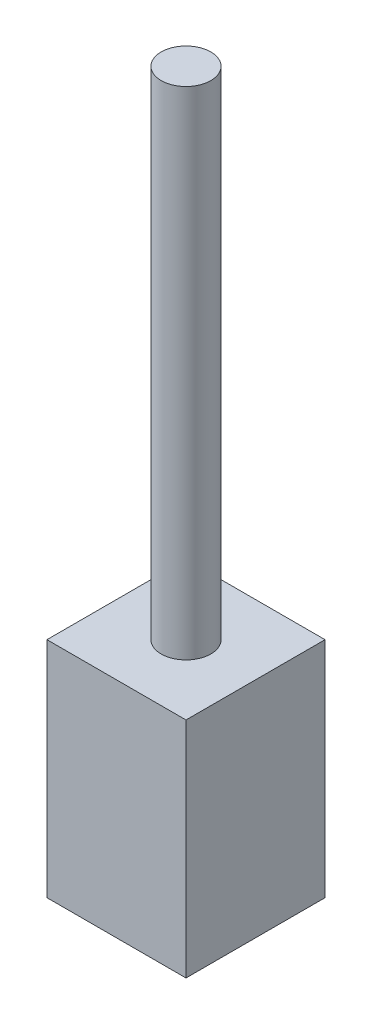
SolidWorks part; units mm, degrees
ref_plane "前视" through (0, 0, 0) normal (0, 0, 1) x (1, 0, 0)
ref_plane "上视" through (0, 0, 0) normal (0, 1, 0) x (1, 0, 0)
ref_plane "右视" through (0, 0, 0) normal (1, 0, 0) x (0, 0, -1)
sketch "Sketch1" plane through (0, 0, 0) normal (0, 1, 0) x (1, 0, 0)
  line L1 (0, 0) -> (28, 0)
  line L2 (0, 0) -> (0, 28)
  line L3 (0, 28) -> (28, 28)
  line L4 (28, 0) -> (28, 28)
  dimension "D1" = 28
  dimension "D2" = 28
extrude "Extrude1" add sketch "Sketch1" along normal blind 45
sketch "Sketch2" plane through (0, 45, 0) normal (0, 1, 0) x (1, 0, 0)
  circle A0 centre (14, 14) radius 5
extrude "Extrude2" add sketch "Sketch2" along normal blind 100
